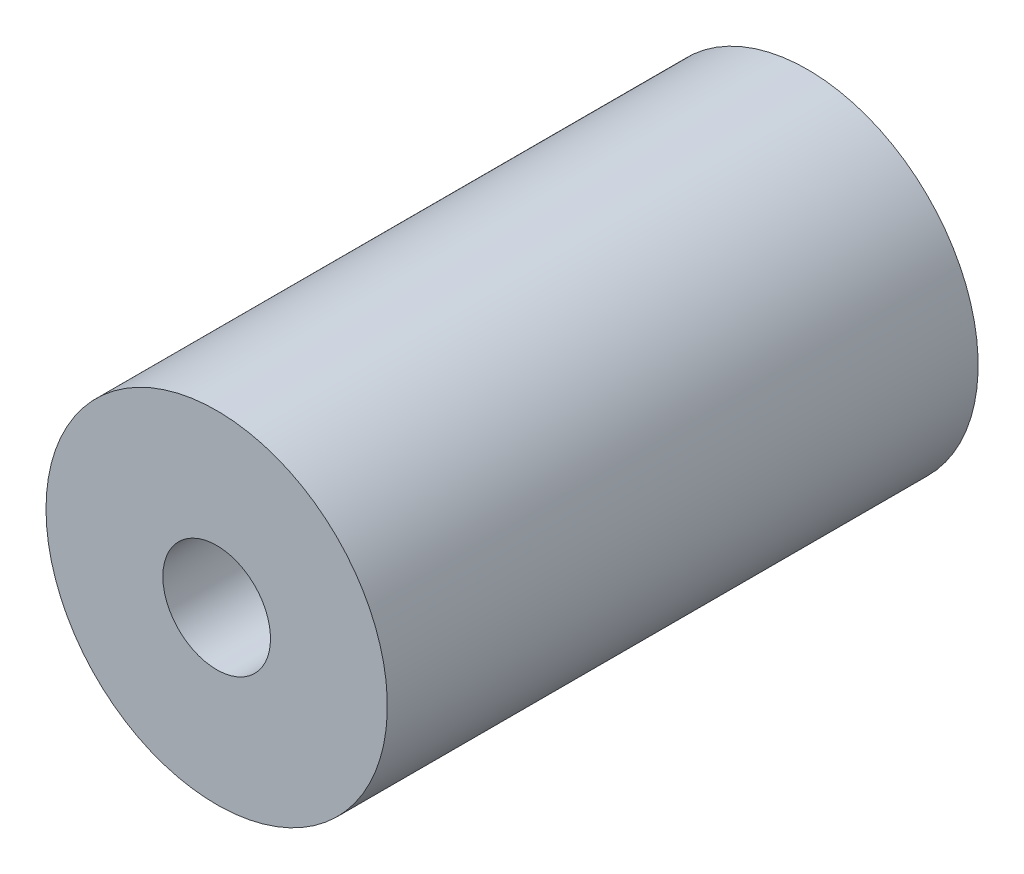
SolidWorks part; units mm, degrees
ref_plane "Спереди" through (0, 0, 0) normal (0, 0, 1) x (1, 0, 0)
ref_plane "Сверху" through (0, 0, 0) normal (0, 1, 0) x (1, 0, 0)
ref_plane "Справа" through (0, 0, 0) normal (1, 0, 0) x (0, 0, -1)
sketch "Эскиз1" plane through (0, 0, 0) normal (0, 0, 1) x (1, 0, 0)
  circle A0 centre (0, 0) radius 13
  circle A1 centre (0, 0) radius 4.1
  dimension "D1" = 8.2
  dimension "D2" = 26
extrude "Вытянуть1" add sketch "Эскиз1" along normal blind 45
